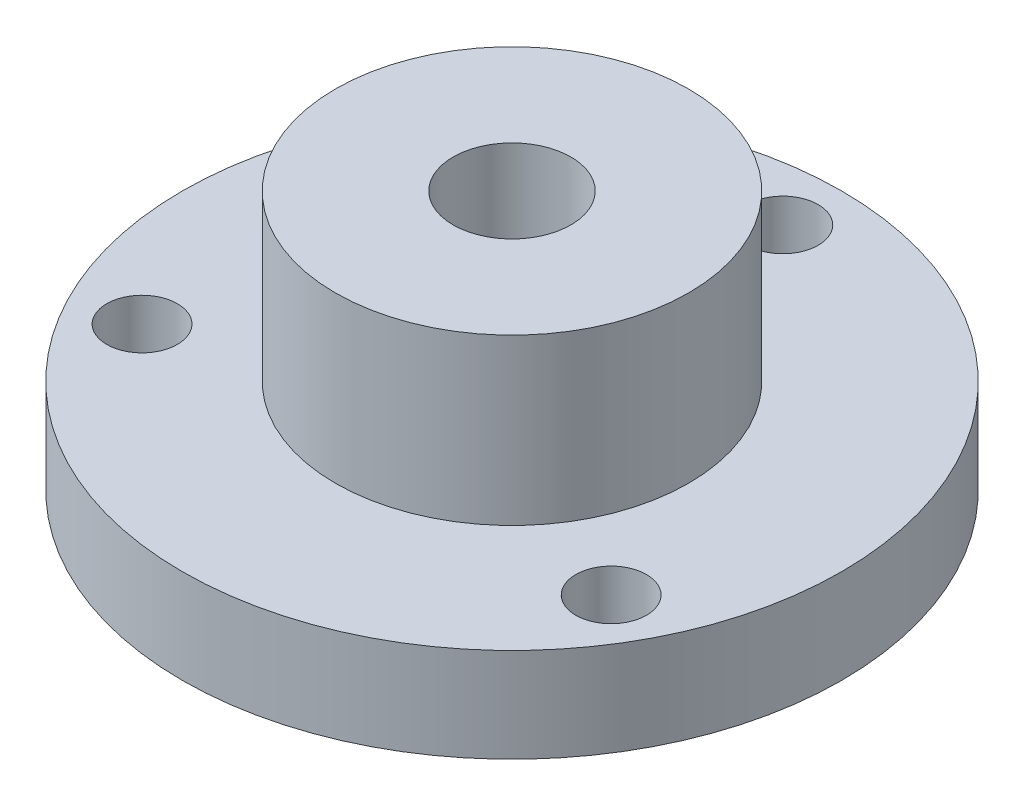
SolidWorks part; units mm, degrees
ref_plane "前视基准面" through (0, 0, 0) normal (0, 0, 1) x (1, 0, 0)
ref_plane "上视基准面" through (0, 0, 0) normal (0, 1, 0) x (1, 0, 0)
ref_plane "右视基准面" through (0, 0, 0) normal (1, 0, 0) x (0, 0, -1)
other "Configuration Table"
sketch "草图1" plane through (0, 0, 0) normal (0, 1, 0) x (1, 0, 0)
  circle A0 centre (0, 0) radius 14
  circle A1 centre (0, 0) radius 11.5 construction
  circle A2 centre (0, 11.5) radius 1.5
  circle A3 centre (9.9593, -5.75) radius 1.5
  circle A4 centre (-9.9593, -5.75) radius 1.5
  point P12 (0, 0)
  dimension "D1" = 28
  dimension "D2" = 23
  dimension "D3" = 3
  dimension "D4" = 3
extrude "凸台-拉伸1" add sketch "草图1" along normal blind 4
sketch "草图2" plane through (0, 4, 0) normal (0, 1, 0) x (1, 0, 0)
  circle A0 centre (0, 0) radius 7.5
  circle A1 centre (0, 0) radius 2.5
  dimension "D1" = 15
  dimension "D2" = 5
extrude "凸台-拉伸2" add sketch "草图2" along normal blind 7
